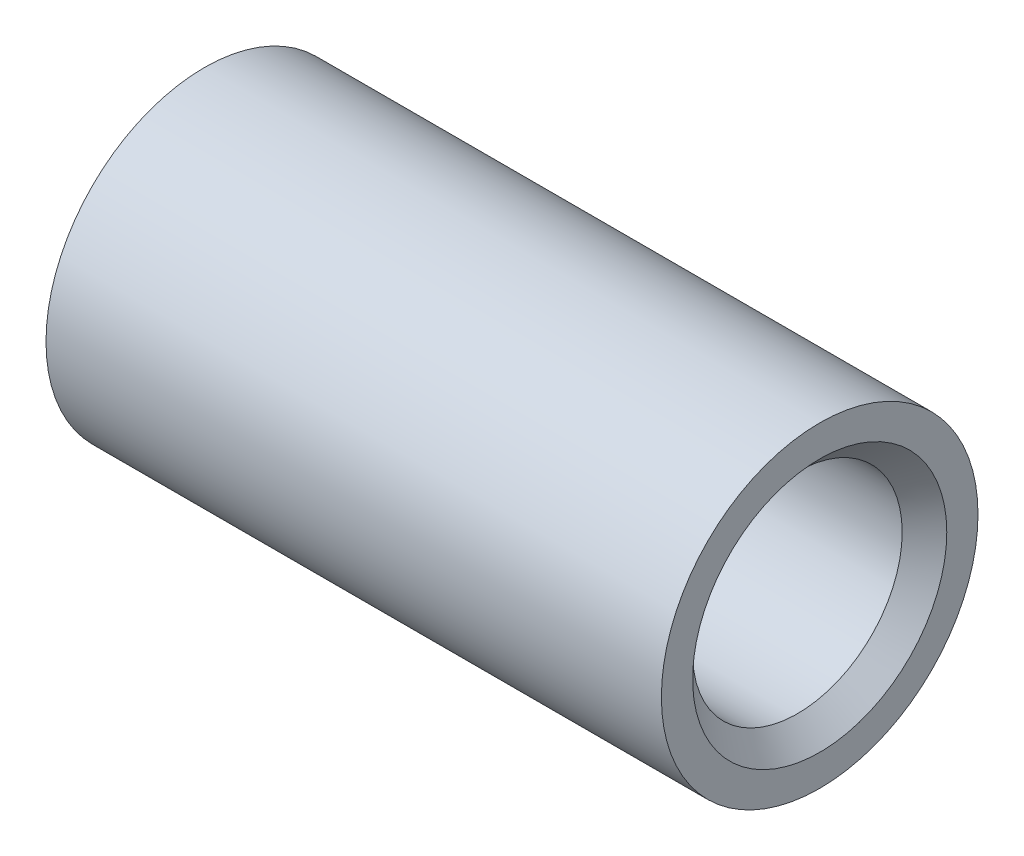
SolidWorks part; units mm, degrees
ref_plane "Front Plane" through (0, 0, 0) normal (0, 0, 1) x (1, 0, 0)
ref_plane "Top Plane" through (0, 0, 0) normal (0, 1, 0) x (1, 0, 0)
ref_plane "Right Plane" through (0, 0, 0) normal (1, 0, 0) x (0, 0, -1)
sketch "Sketch1" plane through (0, 0, 0) normal (0, 0, 1) x (1, 0, 0)
  line L0 (0, 0) -> (-11345.2884, 0) construction
  line L1 (-1.9, 0) -> (-1.9, 2.35)
  line L2 (-1.9, 2.35) -> (-6.4, 2.35)
  line L3 (-6.9, 2.85) -> (-6.9, 3.55)
  line L4 (-6.9, 3.55) -> (6.9, 3.55)
  line L5 (6.9, 3.55) -> (6.9, 2.85)
  line L6 (6.4, 2.35) -> (1.9, 2.35)
  line L7 (1.9, 2.35) -> (1.9, 0)
  line L8 (1.9, 0) -> (-1.9, 0)
  line L9 (0, 0) -> (0, 11345.2884) construction
  line L10 (-6.4, 2.35) -> (-6.9, 2.85)
  line L11 (6.9, 2.85) -> (6.4, 2.35)
  point P6 (-6.9, 2.35)
  point P9 (6.9, 2.35)
  point P13 (0, 3.55)
  dimension "D1" = 2.35
  dimension "D2" = 5
  dimension "D3" = 5
  dimension "D4" = 13.8
  dimension "D5" = 7.1
revolve "Revolve1" add sketch "Sketch1" angle 360 about L0
